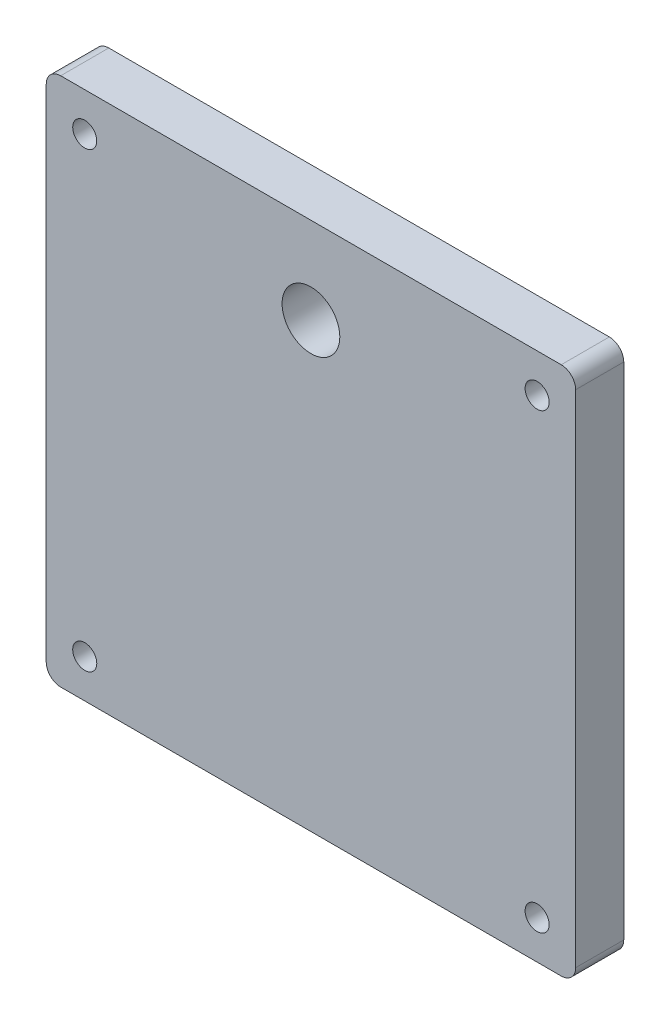
SolidWorks part; units mm, degrees
ref_plane "Front Plane" through (0, 0, 0) normal (0, 0, 1) x (1, 0, 0)
ref_plane "Top Plane" through (0, 0, 0) normal (0, 1, 0) x (1, 0, 0)
ref_plane "Right Plane" through (0, 0, 0) normal (1, 0, 0) x (0, 0, -1)
sketch "Sketch1" plane through (0, 0, 0) normal (0, 0, 1) x (1, 0, 0)
  line L0 (-109.6391, 0) -> (96.9498, 0) construction
  line L1 (-52, 55) -> (52, 55)
  line L2 (-55, 52) -> (-55, -52)
  line L3 (-52, -55) -> (52, -55)
  line L4 (55, 52) -> (55, -52)
  line L5 (0, 89.3167) -> (0, -85.3032) construction
  arc A0 (55, -52) -> (52, -55) centre (52, -52) cw
  arc A1 (-52, -55) -> (-55, -52) centre (-52, -52) cw
  arc A2 (-55, 52) -> (-52, 55) centre (-52, 52) cw
  arc A3 (55, 52) -> (52, 55) centre (52, 52) ccw
  circle A4 centre (47, 47) radius 2.5
  circle A5 centre (47, -47) radius 2.5
  circle A6 centre (-47, -47) radius 2.5
  circle A7 centre (-47, 47) radius 2.5
  circle A8 centre (0, 37) radius 6
  point P9 (-55, -55)
  point P12 (-55, 55)
  point P15 (55, 55)
  dimension "D5" = 3
  dimension "D6" = 8
  dimension "D8" = 5
  dimension "D9" = 12
  dimension "D1" = 110
  dimension "D2" = 55
  dimension "D3" = 110
  dimension "D4" = 55
  dimension "D7" = 8
  dimension "D10" = 37
extrude "Boss-Extrude1" add sketch "Sketch1" along normal blind 10
